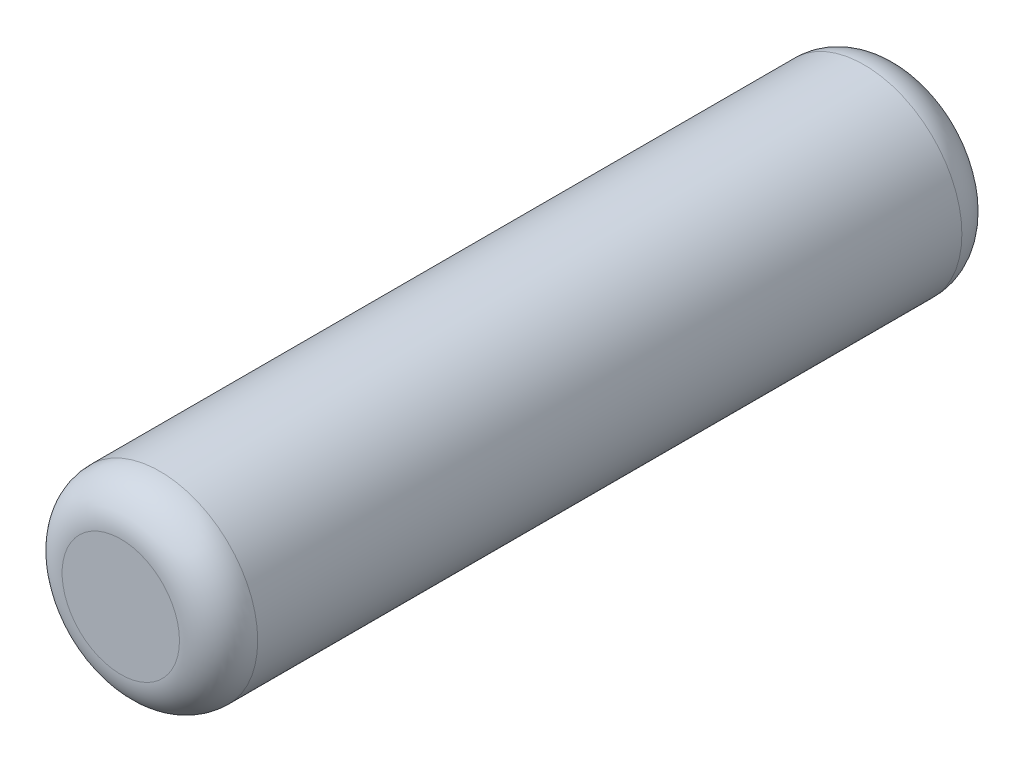
SolidWorks part; units mm, degrees
ref_plane "Plan1" through (0, 0, 0) normal (0, 0, 1) x (1, 0, 0)
ref_plane "Plan2" through (0, 0, 0) normal (0, 1, 0) x (1, 0, 0)
ref_plane "Plan3" through (0, 0, 0) normal (1, 0, 0) x (0, 0, -1)
sketch "Esquisse1" plane through (0, 0, 0) normal (0, 0, 1) x (1, 0, 0)
  circle A0 centre (0, 0) radius 2.5
  dimension "D1" = 5
extrude "Base-Extrusion" add sketch "Esquisse1" along normal blind 20
fillet "Congé1" radius 1
